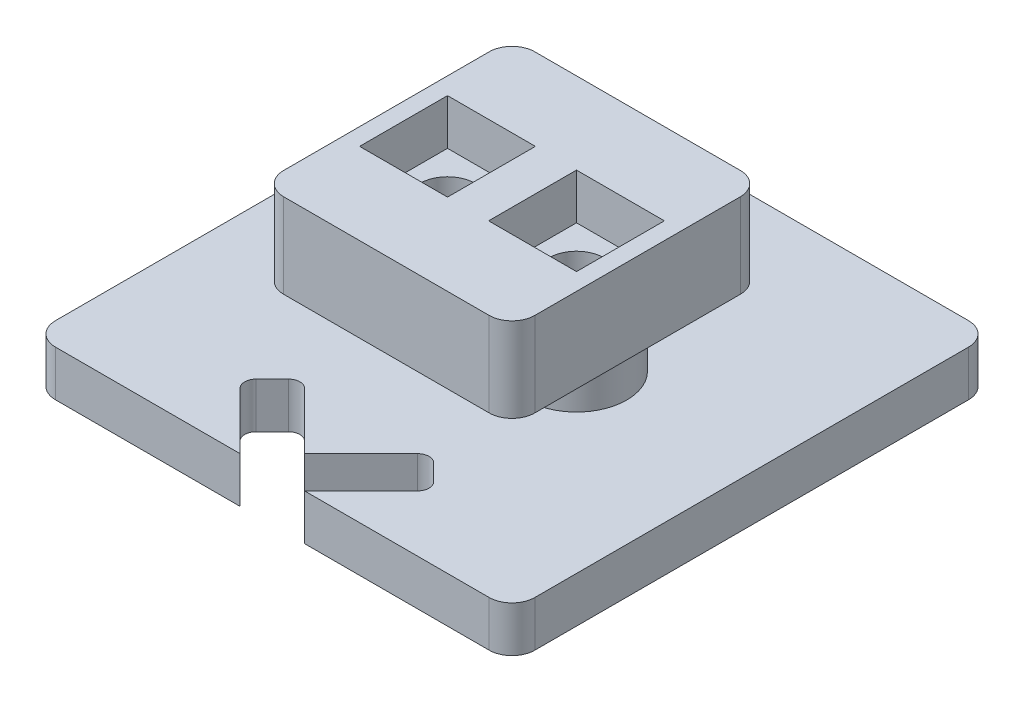
SolidWorks part; units mm, degrees
ref_plane "Front Plane" through (0, 0, 0) normal (0, 0, 1) x (1, 0, 0)
ref_plane "Top Plane" through (0, 0, 0) normal (0, 1, 0) x (1, 0, 0)
ref_plane "Right Plane" through (0, 0, 0) normal (1, 0, 0) x (0, 0, -1)
sketch "Sketch1" plane through (0, 0, 0) normal (0, 1, 0) x (1, 0, 0)
  line L1 (-5.5, -5.5) -> (5.5, -5.5)
  line L2 (-5.5, -5.5) -> (-5.5, 5.5)
  line L3 (-5.5, 5.5) -> (5.5, 5.5)
  line L4 (5.5, -5.5) -> (5.5, 5.5)
  line L5 (-5.5, -5.5) -> (5.5, 5.5) construction
  line L6 (-5.5, 5.5) -> (5.5, -5.5) construction
  point P0 (0, 0)
  dimension "D1" = 11
  dimension "D2" = 11
extrude "Boss-Extrude1" add sketch "Sketch1" along normal blind 3.7
fillet "Fillet1" radius 1 4 edges at (-5.5, 1.85, -5.5) (-5.5, 1.85, 5.5) (5.5, 1.85, -5.5) (5.5, 1.85, 5.5)
sketch "Sketch2" plane through (0, 3.7, 0) normal (0, 1, 0) x (1, 0, 0)
  line L0 (-2.825, 0) -> (2.825, 0) construction
  line L2 (-4.75, -1.925) -> (-0.9, -1.925)
  line L3 (-4.75, -1.925) -> (-4.75, 1.925)
  line L4 (-4.75, 1.925) -> (-0.9, 1.925)
  line L5 (-0.9, -1.925) -> (-0.9, 1.925)
  line L6 (-4.75, -1.925) -> (-0.9, 1.925) construction
  line L7 (-4.75, 1.925) -> (-0.9, -1.925) construction
  line L8 (0.9, -1.925) -> (4.75, -1.925)
  line L9 (0.9, -1.925) -> (0.9, 1.925)
  line L10 (0.9, 1.925) -> (4.75, 1.925)
  line L11 (4.75, -1.925) -> (4.75, 1.925)
  line L12 (0.9, -1.925) -> (4.75, 1.925) construction
  line L13 (0.9, 1.925) -> (4.75, -1.925) construction
  point P4 (0, 0)
  dimension "D1" = 3.85
  dimension "D2" = 3.85
  dimension "D3" = 3.85
  dimension "D4" = 3.85
  dimension "D5" = 5.65
extrude "Cut-Extrude1" cut sketch "Sketch2" against normal blind 2
sketch "Sketch4" plane through (0, 0, 0) normal (0, -1, 0) x (-1, 0, 0)
  line L0 (2.825, 0) -> (-2.825, 0) construction
  circle A0 centre (2.825, 0) radius 2.2
  circle A1 centre (-2.825, 0) radius 2.2
  point P8 (0, 0)
  dimension "D1" = 5.65
  dimension "D2" = 4.4
  dimension "D3" = 4.4
extrude "Boss-Extrude2" add sketch "Sketch4" along normal blind 4
sketch "Sketch5" plane through (0, -4, 0) normal (0, -1, 0) x (-1, 0, 0)
  line L1 (9.5, 10.5) -> (-9.5, 10.5)
  line L2 (10.5, 9.5) -> (10.5, -9.5)
  line L3 (9.5, -10.5) -> (-9.5, -10.5)
  line L4 (-10.5, 9.5) -> (-10.5, -9.5)
  line L5 (10.5, 10.5) -> (-10.5, -10.5) construction
  line L6 (10.5, -10.5) -> (-10.5, 10.5) construction
  arc A0 (10.5, -9.5) -> (9.5, -10.5) centre (9.5, -9.5) cw
  arc A1 (-10.5, -9.5) -> (-9.5, -10.5) centre (-9.5, -9.5) ccw
  arc A2 (-9.5, 10.5) -> (-10.5, 9.5) centre (-9.5, 9.5) ccw
  arc A3 (9.5, 10.5) -> (10.5, 9.5) centre (9.5, 9.5) cw
  point P0 (0, 0)
  dimension "D3" = 1
  dimension "D1" = 21
  dimension "D2" = 21
extrude "Boss-Extrude3" add sketch "Sketch5" against normal blind 2
sketch "Sketch3" plane through (0, 3.7, 0) normal (0, 1, 0) x (1, 0, 0)
  line L0 (-2.825, 0) -> (2.825, 0) construction
  circle A0 centre (-2.825, 0) radius 1.2
  circle A1 centre (2.825, 0) radius 1.2
  point P8 (0, 0)
  dimension "D2" = 2.4
  dimension "D3" = 2.4
  dimension "D1" = 5.65
extrude "Cut-Extrude2" cut sketch "Sketch3" against normal through all
sketch "Sketch7" plane through (0, -2, 0) normal (0, 1, 0) x (1, 0, 0)
  line L0 (9.5, -10.5) -> (-9.5, -10.5) construction
  line L1 (2.8284, -14.7426) -> (4.2426, -13.3284)
  line L2 (2.8284, -14.7426) -> (-3.8891, -8.0251)
  line L3 (-3.8891, -7.318) -> (-3.182, -6.6109)
  line L4 (4.2426, -13.3284) -> (-2.4749, -6.6109)
  line L5 (2.8284, -14.7426) -> (-2.8284, -6.2574) construction
  line L6 (-4.2426, -7.6716) -> (4.2426, -13.3284) construction
  line L8 (-4.2426, -13.3284) -> (-2.8284, -14.7426)
  line L9 (-4.2426, -13.3284) -> (2.4749, -6.6109)
  line L10 (3.182, -6.6109) -> (3.8891, -7.318)
  line L11 (-2.8284, -14.7426) -> (3.8891, -8.0251)
  line L12 (-4.2426, -13.3284) -> (4.2426, -7.6716) construction
  line L13 (2.8284, -6.2574) -> (-2.8284, -14.7426) construction
  arc A0 (-2.4749, -6.6109) -> (-3.182, -6.6109) centre (-2.8284, -6.9645) ccw
  arc A1 (3.8891, -7.318) -> (3.8891, -8.0251) centre (3.5355, -7.6716) cw
  arc A2 (3.182, -6.6109) -> (2.4749, -6.6109) centre (2.8284, -6.9645) ccw
  arc A3 (-3.8891, -7.318) -> (-3.8891, -8.0251) centre (-3.5355, -7.6716) ccw
  point P0 (0, -10.5)
  point P7 (0, -10.5)
  point P12 (-1.4142, -10.5)
  point P13 (1.4142, -10.5)
  line M12 (-9.5, -10.5) -> (9.5, -10.5)
  dimension "D7" = 0.5
  dimension "D8" = 0.5
  dimension "D1" = 2
  dimension "D2" = 45
  dimension "D3" = 2
  dimension "D4" = 45
  dimension "D5" = 4
  dimension "D6" = 4
extrude "Cut-Extrude3" cut sketch "Sketch7" against normal through all contours L10 A2 L9 L4 L11 A1 | L3 A3 L2 L9 L4 A0 | L9 L4 M12
sketch "Sketch8" plane through (0, -4, 0) normal (0, -1, 0) x (1, 0, 0)
  circle A0 centre (-2.825, 0) radius 1.2
  circle A1 centre (-2.825, 0) radius 2.2
  circle A2 centre (2.825, 0) radius 1.2
  circle A3 centre (2.825, 0) radius 2.2
  dimension "D1" = 1
  dimension "D2" = 1
extrude "Boss-Extrude4" add sketch "Sketch8" along normal blind 4
equation "\"D2@Sketch2\"=\"D1@Sketch2\""
equation "\"D3@Sketch2\"=\"D1@Sketch2\""
equation "\"D4@Sketch2\"=\"D1@Sketch2\""
equation "\"D2@Sketch1\"=\"D1@Sketch1\""
equation "\"D3@Sketch3\"=\"D2@Sketch3\""
equation "\"D3@Sketch4\"=\"D2@Sketch4\""
equation "\"D2@Sketch5\"=\"D1@Sketch5\""
equation "\"D3@Sketch7\"=\"D1@Sketch7\""
equation "\"D6@Sketch7\"=\"D5@Sketch7\""
equation "\"D2@Sketch8\"=\"D1@Sketch8\""
